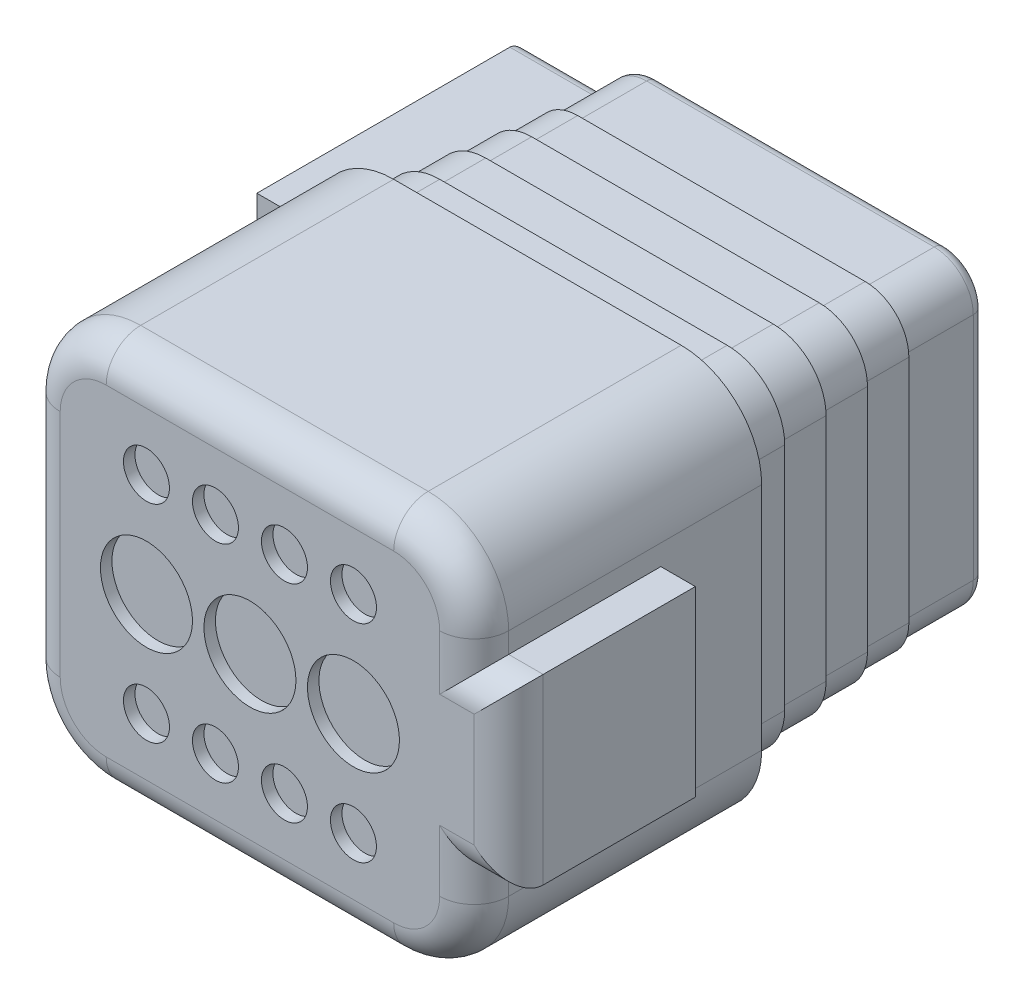
SolidWorks part; units mm, degrees
ref_plane "正面" through (0, 0, 0) normal (0, 0, 1) x (1, 0, 0)
ref_plane "平面" through (0, 0, 0) normal (0, 1, 0) x (1, 0, 0)
ref_plane "右側面" through (0, 0, 0) normal (1, 0, 0) x (0, 0, -1)
sketch "ｽｹｯﾁ1" plane through (0, 0, 0) normal (0, 0, 1) x (1, 0, 0)
  line L1 (7, 0) -> (32, 0)
  line L2 (0, 7) -> (0, 27)
  line L3 (7, 34) -> (32, 34)
  line L4 (39, 7) -> (39, 27)
  arc A0 (32, 34) -> (39, 27) centre (32, 27) cw
  arc A1 (32, 0) -> (39, 7) centre (32, 7) ccw
  arc A2 (7, 0) -> (0, 7) centre (7, 7) cw
  arc A3 (0, 27) -> (7, 34) centre (7, 27) cw
  point P7 (39, 34)
  point P12 (0, 0)
  point P15 (0, 34)
  dimension "D3" = 7
  dimension "D1" = 34
  dimension "D2" = 39
extrude "ﾎﾞｽ - 押し出し1" add sketch "ｽｹｯﾁ1" along normal blind 25
sketch "ｽｹｯﾁ2" plane through (0, 0, 0) normal (0, 0, -1) x (-1, 0, 0)
  line L8 (-37, 27) -> (-37, 7)
  line L9 (-32, 2) -> (-7, 2)
  line L10 (-2, 7) -> (-2, 27)
  line L11 (-7, 32) -> (-32, 32)
  line L12 (-37, 27) -> (-37, 7)
  line L13 (-32, 2) -> (-7, 2)
  line L14 (-2, 7) -> (-2, 27)
  line L15 (-7, 32) -> (-32, 32)
  arc A8 (-32, 32) -> (-37, 27) centre (-32, 27) ccw
  arc A9 (-37, 7) -> (-32, 2) centre (-32, 7) ccw
  arc A10 (-7, 2) -> (-2, 7) centre (-7, 7) ccw
  arc A11 (-2, 27) -> (-7, 32) centre (-7, 27) ccw
  arc A12 (-32, 32) -> (-37, 27) centre (-32, 27) ccw
  arc A13 (-37, 7) -> (-32, 2) centre (-32, 7) ccw
  arc A14 (-7, 2) -> (-2, 7) centre (-7, 7) ccw
  arc A15 (-2, 27) -> (-7, 32) centre (-7, 27) ccw
  dimension "D1" = 2
extrude "ﾎﾞｽ - 押し出し3" add sketch "ｽｹｯﾁ2" along normal blind 4
sketch "ｽｹｯﾁ3" plane through (0, 0, -4) normal (0, 0, -1) x (-1, 0, 0)
  line L8 (-39, 27) -> (-39, 7)
  line L9 (-32, 0) -> (-7, 0)
  line L10 (0, 7) -> (0, 27)
  line L11 (-7, 34) -> (-32, 34)
  line L12 (-39, 27) -> (-39, 7)
  line L13 (-32, 0) -> (-7, 0)
  line L14 (0, 7) -> (0, 27)
  line L15 (-7, 34) -> (-32, 34)
  line L36 (-32, 2.4) -> (-7, 2.4)
  line L37 (-2.4, 7) -> (-2.4, 27)
  line L38 (-7, 31.6) -> (-32, 31.6)
  line L39 (-36.6, 27) -> (-36.6, 7)
  line L40 (-32, 2.4) -> (-7, 2.4)
  line L41 (-2.4, 7) -> (-2.4, 27)
  line L42 (-7, 31.6) -> (-32, 31.6)
  line L43 (-36.6, 27) -> (-36.6, 7)
  arc A8 (-32, 34) -> (-39, 27) centre (-32, 27) ccw
  arc A9 (-39, 7) -> (-32, 0) centre (-32, 7) ccw
  arc A10 (-7, 0) -> (0, 7) centre (-7, 7) ccw
  arc A11 (0, 27) -> (-7, 34) centre (-7, 27) ccw
  arc A12 (-32, 34) -> (-39, 27) centre (-32, 27) ccw
  arc A13 (-39, 7) -> (-32, 0) centre (-32, 7) ccw
  arc A14 (-7, 0) -> (0, 7) centre (-7, 7) ccw
  arc A15 (0, 27) -> (-7, 34) centre (-7, 27) ccw
  arc A32 (-36.6, 7) -> (-32, 2.4) centre (-32, 7) ccw
  arc A33 (-7, 2.4) -> (-2.4, 7) centre (-7, 7) ccw
  arc A34 (-2.4, 27) -> (-7, 31.6) centre (-7, 27) ccw
  arc A35 (-32, 31.6) -> (-36.6, 27) centre (-32, 27) ccw
  arc A36 (-36.6, 7) -> (-32, 2.4) centre (-32, 7) ccw
  arc A37 (-7, 2.4) -> (-2.4, 7) centre (-7, 7) ccw
  arc A38 (-2.4, 27) -> (-7, 31.6) centre (-7, 27) ccw
  arc A39 (-32, 31.6) -> (-36.6, 27) centre (-32, 27) ccw
  dimension "D1" = 2
  dimension "D2" = 0.4
extrude "ﾎﾞｽ - 押し出し4" add sketch "ｽｹｯﾁ3" along normal blind 4 contours L43 A36 L40 A37 L41 A38 L42 A39
sketch "ｽｹｯﾁ4" plane through (0, 0, -8) normal (0, 0, -1) x (-1, 0, 0)
  line L8 (-36.2, 27) -> (-36.2, 7)
  line L9 (-32, 2.8) -> (-7, 2.8)
  line L10 (-2.8, 7) -> (-2.8, 27)
  line L11 (-7, 31.2) -> (-32, 31.2)
  line L12 (-36.2, 27) -> (-36.2, 7)
  line L13 (-32, 2.8) -> (-7, 2.8)
  line L14 (-2.8, 7) -> (-2.8, 27)
  line L15 (-7, 31.2) -> (-32, 31.2)
  arc A8 (-32, 31.2) -> (-36.2, 27) centre (-32, 27) ccw
  arc A9 (-36.2, 7) -> (-32, 2.8) centre (-32, 7) ccw
  arc A10 (-7, 2.8) -> (-2.8, 7) centre (-7, 7) ccw
  arc A11 (-2.8, 27) -> (-7, 31.2) centre (-7, 27) ccw
  arc A12 (-32, 31.2) -> (-36.2, 27) centre (-32, 27) ccw
  arc A13 (-36.2, 7) -> (-32, 2.8) centre (-32, 7) ccw
  arc A14 (-7, 2.8) -> (-2.8, 7) centre (-7, 7) ccw
  arc A15 (-2.8, 27) -> (-7, 31.2) centre (-7, 27) ccw
  dimension "D1" = 0.4
extrude "ﾎﾞｽ - 押し出し5" add sketch "ｽｹｯﾁ4" along normal blind 4
sketch "ｽｹｯﾁ5" plane through (0, 0, -12) normal (0, 0, -1) x (-1, 0, 0)
  line L8 (-35.8, 27) -> (-35.8, 7)
  line L9 (-32, 3.2) -> (-7, 3.2)
  line L10 (-3.2, 7) -> (-3.2, 27)
  line L11 (-7, 30.8) -> (-32, 30.8)
  line L12 (-35.8, 27) -> (-35.8, 7)
  line L13 (-32, 3.2) -> (-7, 3.2)
  line L14 (-3.2, 7) -> (-3.2, 27)
  line L15 (-7, 30.8) -> (-32, 30.8)
  arc A8 (-32, 30.8) -> (-35.8, 27) centre (-32, 27) ccw
  arc A9 (-35.8, 7) -> (-32, 3.2) centre (-32, 7) ccw
  arc A10 (-7, 3.2) -> (-3.2, 7) centre (-7, 7) ccw
  arc A11 (-3.2, 27) -> (-7, 30.8) centre (-7, 27) ccw
  arc A12 (-32, 30.8) -> (-35.8, 27) centre (-32, 27) ccw
  arc A13 (-35.8, 7) -> (-32, 3.2) centre (-32, 7) ccw
  arc A14 (-7, 3.2) -> (-3.2, 7) centre (-7, 7) ccw
  arc A15 (-3.2, 27) -> (-7, 30.8) centre (-7, 27) ccw
  dimension "D1" = 0.4
extrude "ﾎﾞｽ - 押し出し6" add sketch "ｽｹｯﾁ5" along normal blind 4
sketch "ｽｹｯﾁ6" plane through (0, 0, -16) normal (0, 0, -1) x (-1, 0, 0)
  line L8 (-35.4, 27) -> (-35.4, 7)
  line L9 (-32, 3.6) -> (-7, 3.6)
  line L10 (-3.6, 7) -> (-3.6, 27)
  line L11 (-7, 30.4) -> (-32, 30.4)
  line L12 (-35.4, 27) -> (-35.4, 7)
  line L13 (-32, 3.6) -> (-7, 3.6)
  line L14 (-3.6, 7) -> (-3.6, 27)
  line L15 (-7, 30.4) -> (-32, 30.4)
  arc A8 (-32, 30.4) -> (-35.4, 27) centre (-32, 27) ccw
  arc A9 (-35.4, 7) -> (-32, 3.6) centre (-32, 7) ccw
  arc A10 (-7, 3.6) -> (-3.6, 7) centre (-7, 7) ccw
  arc A11 (-3.6, 27) -> (-7, 30.4) centre (-7, 27) ccw
  arc A12 (-32, 30.4) -> (-35.4, 27) centre (-32, 27) ccw
  arc A13 (-35.4, 7) -> (-32, 3.6) centre (-32, 7) ccw
  arc A14 (-7, 3.6) -> (-3.6, 7) centre (-7, 7) ccw
  arc A15 (-3.6, 27) -> (-7, 30.4) centre (-7, 27) ccw
  dimension "D1" = 0.4
extrude "ﾎﾞｽ - 押し出し7" add sketch "ｽｹｯﾁ6" along normal blind 7
sketch "ｽｹｯﾁ7" plane through (3.6, 0, 0) normal (-1, 0, 0) x (0, 0, 1)
  line L1 (0, 27) -> (-23, 27)
  line L2 (0, 27) -> (0, 7)
  line L3 (0, 7) -> (-23, 7)
  line L4 (-23, 27) -> (-23, 7)
extrude "ﾎﾞｽ - 押し出し8" add sketch "ｽｹｯﾁ7" along normal blind 8.5
sketch "ｽｹｯﾁ8" plane through (39, 0, 0) normal (1, 0, 0) x (0, 0, -1)
  line L0 (-25, 17.2832) -> (0, 17.2832) construction
  line L1 (-25, 7) -> (-25, 27) construction
  line L2 (0, 7) -> (0, 27) construction
  line L4 (-8.7683, 25.2135) -> (-25, 25.2135)
  line L5 (-8.7683, 25.2135) -> (-8.7683, 9.353)
  line L6 (-8.7683, 9.353) -> (-25, 9.353)
  line L7 (-25, 25.2135) -> (-25, 9.353)
  line L8 (-8.7683, 25.2135) -> (-25, 9.353) construction
  line L9 (-8.7683, 9.353) -> (-25, 25.2135) construction
  point P6 (-16.8841, 17.2832)
extrude "ﾎﾞｽ - 押し出し9" add sketch "ｽｹｯﾁ8" along normal blind 3
fillet "ﾌｨﾚｯﾄ1" radius 3 12 edges at (39, 26.1067, 25) (40.5, 25.2135, 25) (42, 17.2832, 25) (40.5, 9.353, 25) (39, 8.1765, 25) (36.9497, 2.0503, 25) (19.5, 0, 25) (2.0503, 2.0503, 25) (0, 17, 25) (2.0503, 31.9497, 25) (19.5, 34, 25) (36.9497, 31.9497, 25)
fillet "ﾌｨﾚｯﾄ2" radius 1 10 edges at (19.5, 30.4, -23) (4.5958, 29.4042, -23) (-0.65, 27, -23) (-4.9, 17, -23) (-0.65, 7, -23) (4.5958, 4.5958, -23) (19.5, 3.6, -23) (34.4042, 4.5958, -23) (35.4, 17, -23) (34.4042, 29.4042, -23)
sketch "ｽｹｯﾁ9" plane through (0, 0, 25) normal (0, 0, 1) x (1, 0, 0)
  line L0 (3, 17) -> (39, 17) construction
  line L1 (3, 27) -> (3, 7) construction
  line L2 (39, 12.353) -> (39, 22.2135) construction
  line L3 (19.5, 31) -> (19.5, 3) construction
  line L4 (32, 31) -> (7, 31) construction
  line L5 (7, 3) -> (32, 3) construction
  circle A0 centre (19.5, 17) radius 4
  circle A1 centre (28.5, 17) radius 4
  circle A2 centre (10.5, 17) radius 4
  circle A3 centre (16.5, 8) radius 2
  circle A4 centre (10.5, 8) radius 2
  circle A5 centre (22.5, 8) radius 2
  circle A6 centre (28.5, 8) radius 2
  circle A7 centre (28.5, 26) radius 2
  circle A8 centre (22.5, 26) radius 2
  circle A9 centre (16.5, 26) radius 2
  circle A10 centre (10.5, 26) radius 2
  dimension "D1" = 8
  dimension "D4" = 4
  dimension "D8" = 6
  dimension "D3" = 9
  dimension "D5" = 3
  dimension "D6" = 9
  dimension "D2" = 2
  dimension "D7" = 2
extrude "ｶｯﾄ - 押し出し1" cut sketch "ｽｹｯﾁ9" against normal blind 1
sketch "ｽｹｯﾁ10" plane through (0, 0, -23) normal (0, 0, -1) x (-1, 0, 0)
  line L0 (-34.4, 17) -> (3.9, 17) construction
  line L1 (-34.4, 27) -> (-34.4, 7) construction
  line L2 (3.9, 8) -> (3.9, 26) construction
  line L3 (-19.5, 29.4) -> (-19.5, 4.6) construction
  line L4 (-7, 29.4) -> (-32, 29.4) construction
  line L5 (-32, 4.6) -> (-7, 4.6) construction
  circle A0 centre (-19.5, 17) radius 4
  circle A1 centre (-10.5, 17) radius 4
  circle A2 centre (-28.5, 17) radius 4
  circle A3 centre (-16.5, 26) radius 2
  circle A4 centre (-10.5, 26) radius 2
  circle A5 centre (-28.5, 26) radius 2
  circle A6 centre (-22.5, 26) radius 2
  circle A7 centre (-10.5, 8) radius 2
  circle A8 centre (-16.5, 8) radius 2
  circle A9 centre (-22.5, 8) radius 2
  circle A10 centre (-28.5, 8) radius 2
  dimension "D1" = 8
  dimension "D6" = 4
  dimension "D2" = 2
  dimension "D3" = 9
  dimension "D5" = 9
  dimension "D7" = 3
  dimension "D8" = 9
  dimension "D10" = 6
  dimension "D4" = 2
  dimension "D9" = 2
extrude "ｶｯﾄ - 押し出し2" cut sketch "ｽｹｯﾁ10" against normal blind 1
